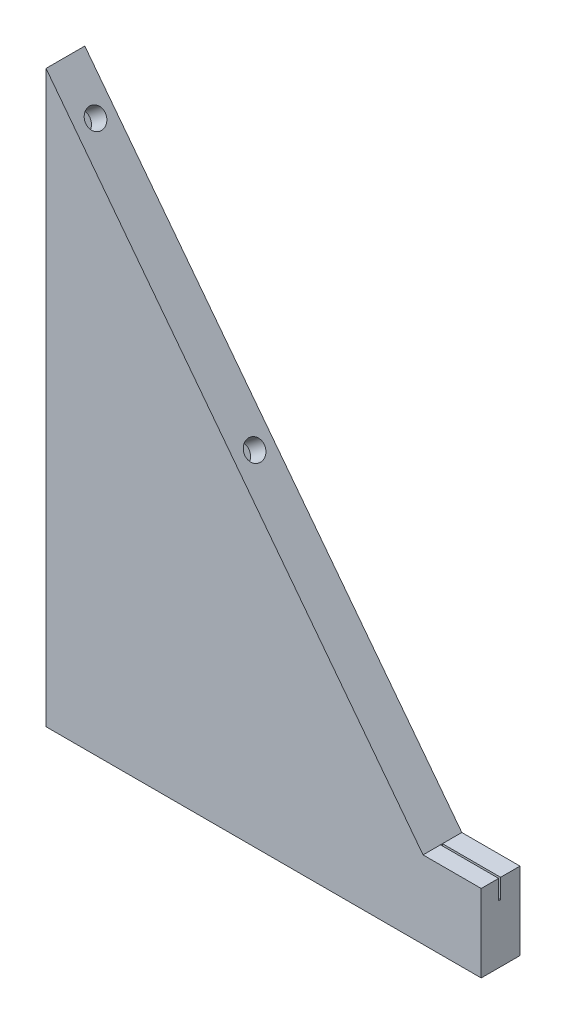
SolidWorks part; units mm, degrees
material "Brass"
ref_plane "Front Plane" through (0, 0, 0) normal (0, 0, 1) x (1, 0, 0)
ref_plane "Top Plane" through (0, 0, 0) normal (0, 1, 0) x (1, 0, 0)
ref_plane "Right Plane" through (0, 0, 0) normal (1, 0, 0) x (0, 0, -1)
sketch "Sketch1" plane through (0, 0, 0) normal (0, 0, 1) x (1, 0, 0)
  line L0 (-1000, 0) -> (49000, 0) construction
  line L1 (0, -1000) -> (0, 49000) construction
  line L2 (-61.7516, 93.3802) -> (-61.7516, -93.3802)
  line L3 (-61.7516, -93.3802) -> (61.7516, -93.3802)
  line L4 (61.7516, -67.9802) -> (80.8016, -67.9802)
  line L5 (61.7516, -67.9802) -> (-61.7516, 93.3802)
  line L6 (80.8016, -67.9802) -> (80.8016, -93.3802)
  line L7 (-938.2484, -67.9802) -> (49061.7516, -67.9802) construction
  line L8 (80.8016, -93.3802) -> (61.7516, -93.3802)
  dimension "D1" = 203.2
  dimension "D2" = 25.4
  dimension "D3" = 37.43
  dimension "D4" = 19.05
extrude "Extrude1" add sketch "Sketch1" along normal blind 12.7
sketch "Sketch3" plane through (0, -93.3802, 0) normal (0, -1, 0) x (1, 0, 0)
  line L1 (-72.8938, 6.35) -> (68.3178, 6.35) construction
  circle A0 centre (-53.5005, 6.35) radius 3.175
  circle A1 centre (48.0995, 6.35) radius 3.175
  dimension "D2" = 6.35
  dimension "D3" = 6.35
  dimension "D1" = 101.6
extrude "Extrude2" cut sketch "Sketch3" against normal blind 12.7
sketch "Sketch4" plane through (6.1296, 4.6915, 0) normal (0.7941, 0.6078, 0) x (0, 0, -1)
  line L0 (-1000, 0) -> (49000, 0) construction
  line L1 (-6.1287, -1030.4896) -> (-6.1287, 48969.5104) construction
  line L2 (-12.7, -91.515) -> (0, -91.515) construction
  circle A0 centre (-6.1287, 95.81) radius 3.175
  circle A1 centre (-6.1287, 10.085) radius 3.175
  dimension "D3" = 6.35
  dimension "D4" = 6.35
  dimension "D1" = 85.725
  dimension "D2" = 101.6
extrude "Extrude3" cut sketch "Sketch4" against normal blind 6.35
sketch "Sketch6" plane through (0, -67.9802, 0) normal (0, 1, 0) x (1, 0, 0)
  line L0 (61.7516, -12.7) -> (61.7516, 0) construction
  line L1 (61.7516, -6.985) -> (80.8016, -6.985)
  line L2 (61.7516, -6.985) -> (61.7516, -6.35)
  line L3 (61.7516, -6.35) -> (80.8016, -6.35)
  line L4 (80.8016, -6.985) -> (80.8016, -6.35)
  line L5 (80.8016, -12.7) -> (80.8016, 0) construction
  line L6 (80.8016, 0) -> (61.7516, 0) construction
  dimension "D1" = 0.635
  dimension "D2" = 6.35
extrude "Extrude4" cut sketch "Sketch6" against normal blind 6.35
